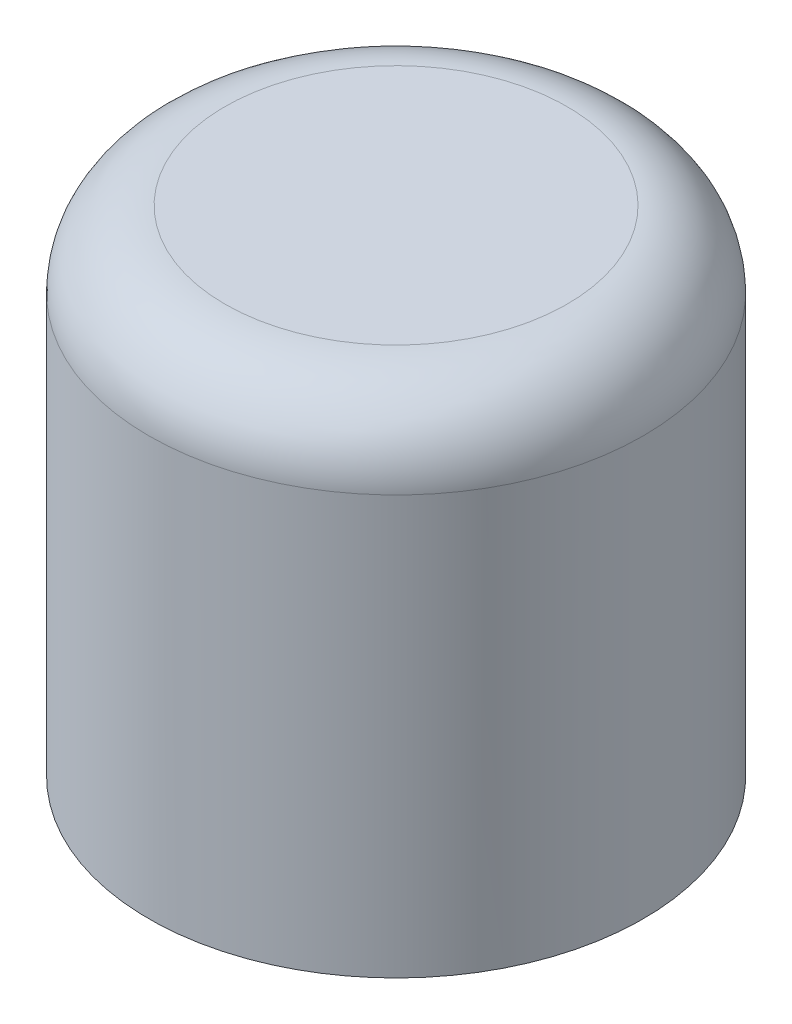
SolidWorks part; units mm, degrees
ref_plane "Front Plane" through (0, 0, 0) normal (0, 0, 1) x (1, 0, 0)
ref_plane "Top Plane" through (0, 0, 0) normal (0, 1, 0) x (1, 0, 0)
ref_plane "Right Plane" through (0, 0, 0) normal (1, 0, 0) x (0, 0, -1)
sketch "Sketch1" plane through (0, 0, 0) normal (0, 1, 0) x (1, 0, 0)
  circle A0 centre (0, 0) radius 6.5
  dimension "D1" = 13
extrude "Boss-Extrude1" add sketch "Sketch1" along normal blind 13
fillet "Fillet1" radius 2 1 edges at (0, 13, 6.5)
